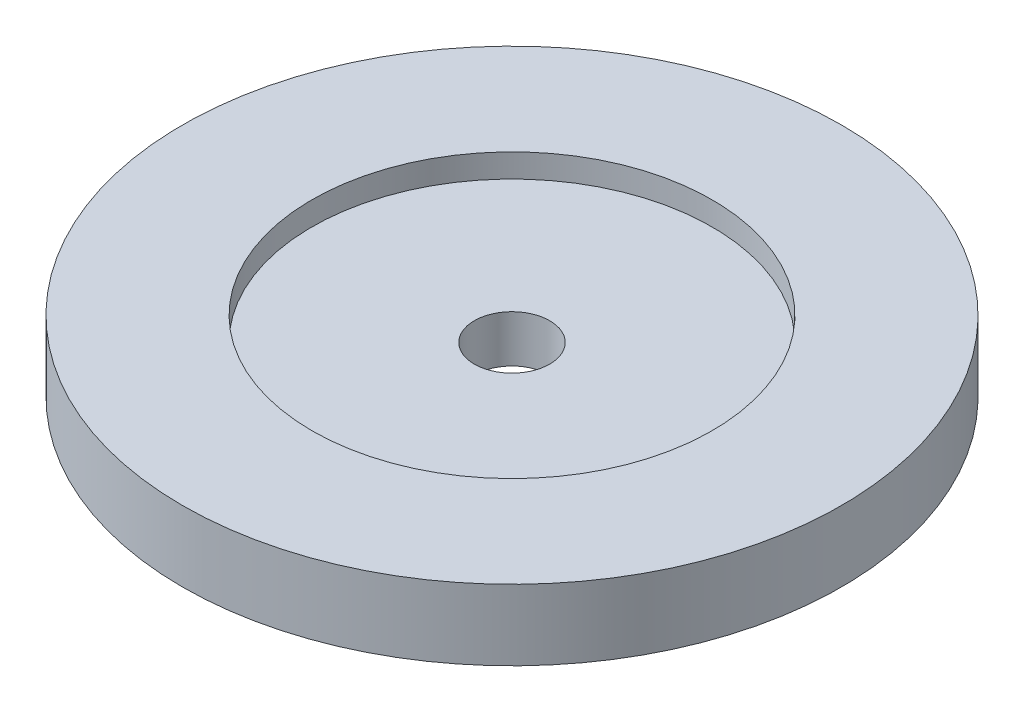
SolidWorks part; units mm, degrees
ref_plane "Front Plane" through (0, 0, 0) normal (0, 0, 1) x (1, 0, 0)
ref_plane "Top Plane" through (0, 0, 0) normal (0, 1, 0) x (1, 0, 0)
ref_plane "Right Plane" through (0, 0, 0) normal (1, 0, 0) x (0, 0, -1)
sketch "Sketch1" plane through (0, 0, 0) normal (0, 1, 0) x (1, 0, 0)
  circle A0 centre (0, 0) radius 1.6
  circle A1 centre (0, 0) radius 14
  dimension "D1" = 3.2
  dimension "D2" = 28
extrude "Boss-Extrude1" add sketch "Sketch1" along normal blind 3
sketch "Sketch2" plane through (0, 3, 0) normal (0, 1, 0) x (1, 0, 0)
  circle A0 centre (0, 0) radius 8.5
  dimension "D1" = 17
extrude "Cut-Extrude1" cut sketch "Sketch2" against normal blind 1
